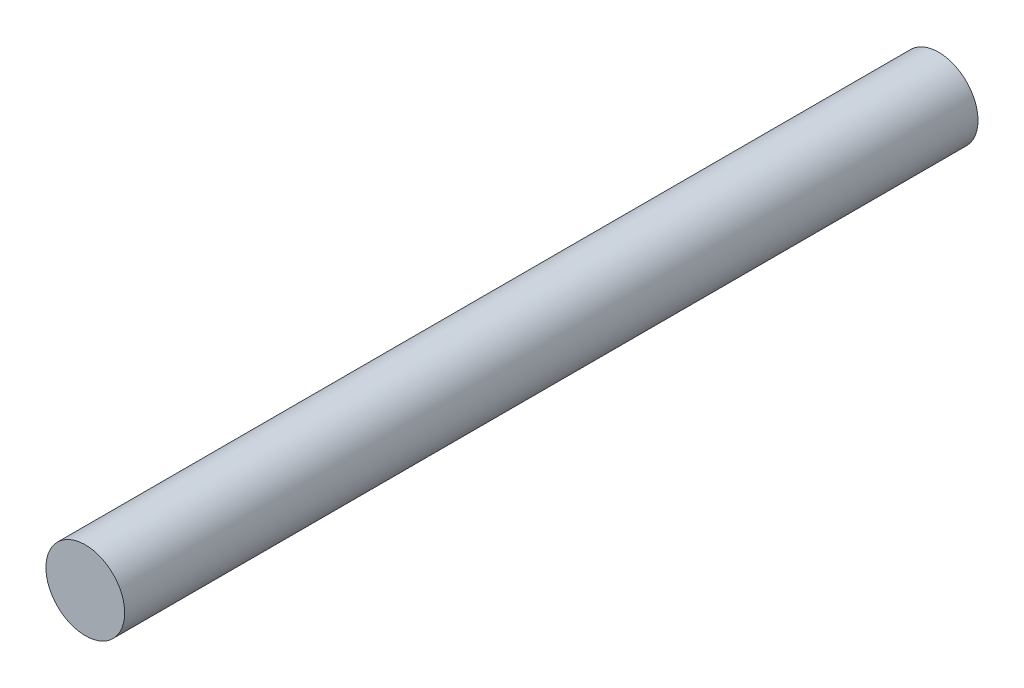
SolidWorks part; units mm, degrees
ref_plane "前视基准面" through (0, 0, 0) normal (0, 0, 1) x (1, 0, 0)
ref_plane "上视基准面" through (0, 0, 0) normal (0, 1, 0) x (1, 0, 0)
ref_plane "右视基准面" through (0, 0, 0) normal (1, 0, 0) x (0, 0, -1)
other "Configuration Table"
sketch "草图1" plane through (0, 0, 0) normal (0, 0, 1) x (1, 0, 0)
  circle A0 centre (0, 0) radius 3
extrude "凸台-拉伸1" add sketch "草图1" along normal blind 65
